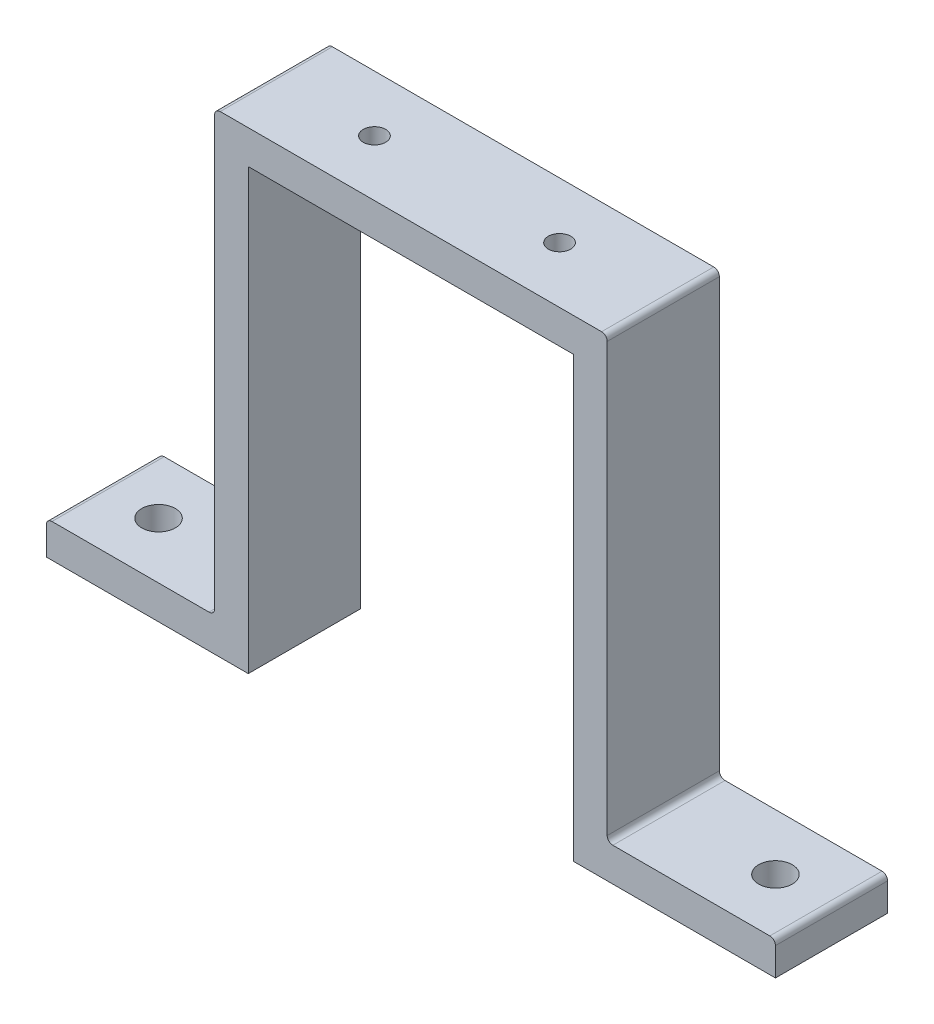
SolidWorks part; units mm, degrees
material "ABS"
ref_plane "Plan de face" through (0, 0, 0) normal (0, 0, 1) x (1, 0, 0)
ref_plane "Plan de dessus" through (0, 0, 0) normal (0, 1, 0) x (1, 0, 0)
ref_plane "Plan de droite" through (0, 0, 0) normal (1, 0, 0) x (0, 0, -1)
sketch "Esquisse6" plane through (0, 0, 0) normal (0, 0, 1) x (1, 0, 0)
  line L0 (-32.5, -39.15) -> (-14.5, -39.15)
  line L1 (-14.5, -39.15) -> (-14.5, 0)
  line L2 (-14.5, 0) -> (14.5, 0)
  line L3 (14.5, 0) -> (14.5, -39.15)
  line L8 (17.5, 3) -> (-17.5, 3)
  line L9 (-17.5, 3) -> (-17.5, -36.15)
  line L10 (-17.5, -36.15) -> (-32.5, -36.15)
  line L11 (-32.5, -36.15) -> (-32.5, -39.15)
  line L12 (17.5, 3) -> (17.5, -36.15)
  line L13 (32.5, -36.15) -> (32.5, -39.15)
  line L14 (32.5, -39.15) -> (14.5, -39.15)
  line L15 (17.5, -36.15) -> (32.5, -36.15)
  point P11 (0, 0)
  dimension "D1" = 3
  dimension "D2" = 3
  dimension "D3" = 3
  dimension "D4" = 15
  dimension "D5" = 29
  dimension "D6" = 39.15
extrude "Boss.-Extru.3" add sketch "Esquisse6" along normal blind 10
sketch "Esquisse7" plane through (0, 3, 0) normal (0, 1, 0) x (1, 0, 0)
  line L1 (17.5, -10) -> (17.5, 0) construction
  line L2 (-17.5, -10) -> (-17.5, 0) construction
  circle A0 centre (-8.25, -5) radius 1
  circle A1 centre (8.25, -5) radius 1
  dimension "D1" = 2
  dimension "D2" = 9.25
  dimension "D3" = 16.5
  dimension "D4" = 9.25
extrude "Enlèv. mat.-Extru.1" cut sketch "Esquisse7" against normal up to next
sketch "Esquisse8" plane through (0, -36.15, 0) normal (0, 1, 0) x (1, 0, 0)
  line L0 (32.5, -10) -> (32.5, 0) construction
  line L2 (-32.5, -10) -> (-32.5, 0) construction
  circle A0 centre (27.5, -5) radius 1.5
  circle A1 centre (-27.5, -5) radius 1.5
  dimension "D1" = 3
  dimension "D2" = 5
  dimension "D3" = 5
extrude "Enlèv. mat.-Extru.2" cut sketch "Esquisse8" against normal up to next contours A1 | A0
fillet "Congé8" radius 0.5 6 edges at (-32.5, -36.15, 5) (32.5, -36.15, 5) (-17.5, -36.15, 5) (-17.5, 3, 5) (17.5, -36.15, 5) (17.5, 3, 5)
